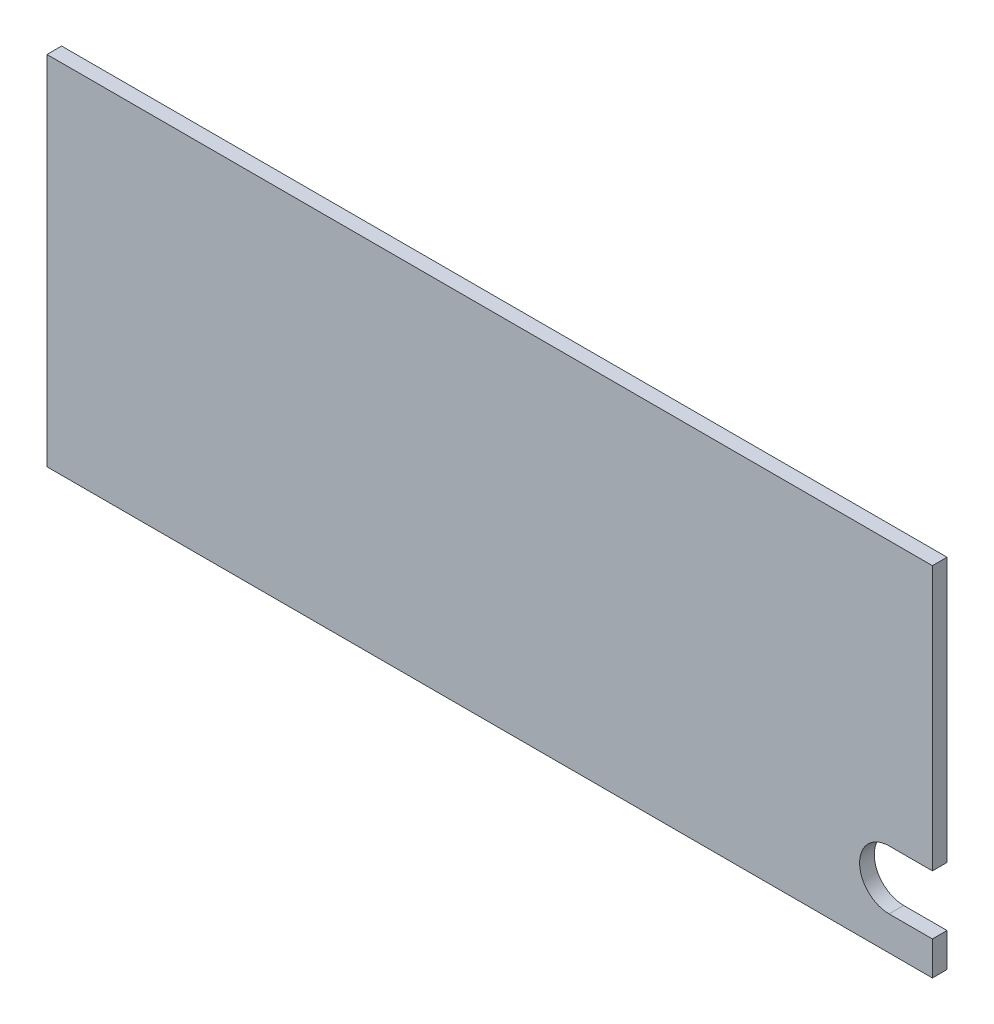
SolidWorks part; units mm, degrees
ref_plane "Piano frontale" through (0, 0, 0) normal (0, 0, 1) x (1, 0, 0)
ref_plane "Piano superiore" through (0, 0, 0) normal (0, 1, 0) x (1, 0, 0)
ref_plane "Piano destro" through (0, 0, 0) normal (1, 0, 0) x (0, 0, -1)
sketch "Schizzo1" plane through (0, 0, 0) normal (0, 0, 1) x (1, 0, 0)
  line L1 (0, 0) -> (121, 0)
  line L2 (0, 0) -> (0, 48.8)
  line L3 (0, 48.8) -> (121, 48.8)
  line L4 (121, 0) -> (121, 48.8)
  dimension "D1" = 121
  dimension "D2" = 48.8
extrude "Estrusione-Estrusione1" add sketch "Schizzo1" along normal blind 2
sketch "Schizzo2" plane through (0, 0, 2) normal (0, 0, 1) x (1, 0, 0)
  line L0 (126.9225, 8.6484) -> (115.0775, 8.6484) construction
  line L2 (126.9225, 4.6229) -> (115.0775, 4.6229)
  line L3 (126.9225, 12.6738) -> (115.0775, 12.6738)
  line L5 (121, 0) -> (121, 48.8) construction
  arc A0 (126.9225, 4.6229) -> (126.9225, 12.6738) centre (126.9225, 8.6484) ccw
  arc A1 (115.0775, 12.6738) -> (115.0775, 4.6229) centre (115.0775, 8.6484) ccw
  point P2 (0, 0)
  point P4 (121, 8.6484)
extrude "Taglio-Estrusione1" cut sketch "Schizzo2" against normal blind 12
